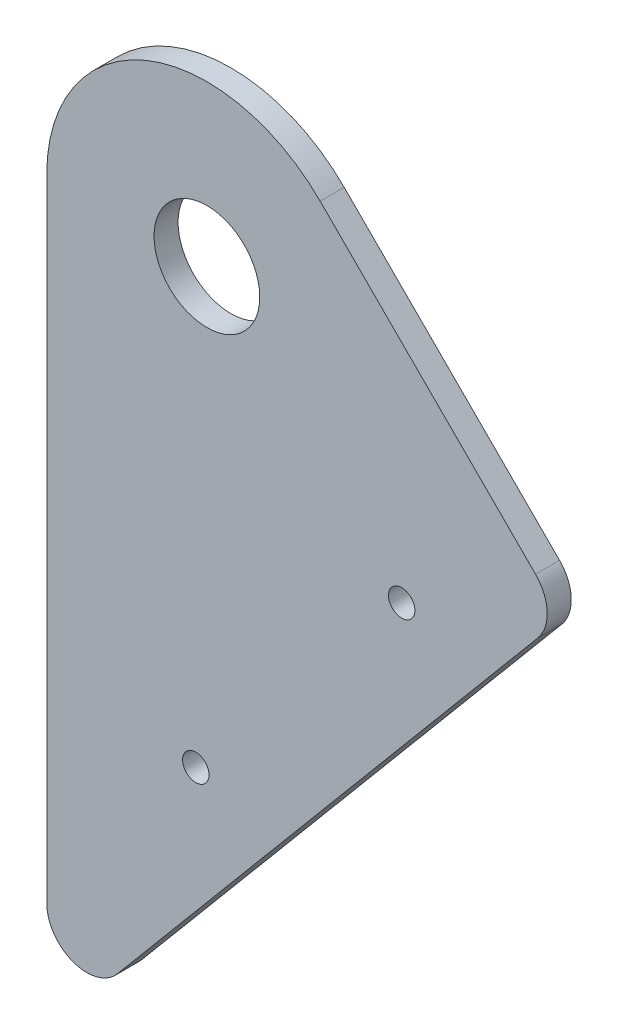
SolidWorks part; units mm, degrees
material "Thornel Mat VMA"
ref_plane "前视基准面" through (0, 0, 0) normal (0, 0, 1) x (1, 0, 0)
ref_plane "上视基准面" through (0, 0, 0) normal (0, 1, 0) x (1, 0, 0)
ref_plane "右视基准面" through (0, 0, 0) normal (1, 0, 0) x (0, 0, -1)
sketch "草图1" plane through (0, 0, 0) normal (0, 0, 1) x (1, 0, 0)
  line L0 (0, 0) -> (64.2788, 76.6044)
  line L1 (64.2788, 76.6044) -> (34.1421, 106.7411)
  line L2 (0, 92.5989) -> (0, 0)
  line L3 (0, 15.5572) -> (57.1807, 83.7025) construction
  arc A0 (34.1421, 106.7411) -> (0, 92.5989) centre (20, 92.5989) ccw
  circle A1 centre (20, 92.5989) radius 6.6
  circle A2 centre (18.6134, 37.7399) radius 1.65
  circle A3 centre (44.3249, 68.3816) radius 1.65
  dimension "D4" = 20
  dimension "D6" = 13.2
  dimension "D7" = 3.3
  dimension "D8" = 40
  dimension "D9" = 20
  dimension "D1" = 40
  dimension "D2" = 45
  dimension "D3" = 100
  dimension "D5" = 10
extrude "凸台-拉伸1" add sketch "草图1" along normal blind 3 contours L1 A0 L2 L3 A1 | L3 L2 L0 L1 A3 A2
fillet "圆角1" radius 5 2 edges at (64.2788, 76.6044, 1.5) (0, 0, 1.5)
